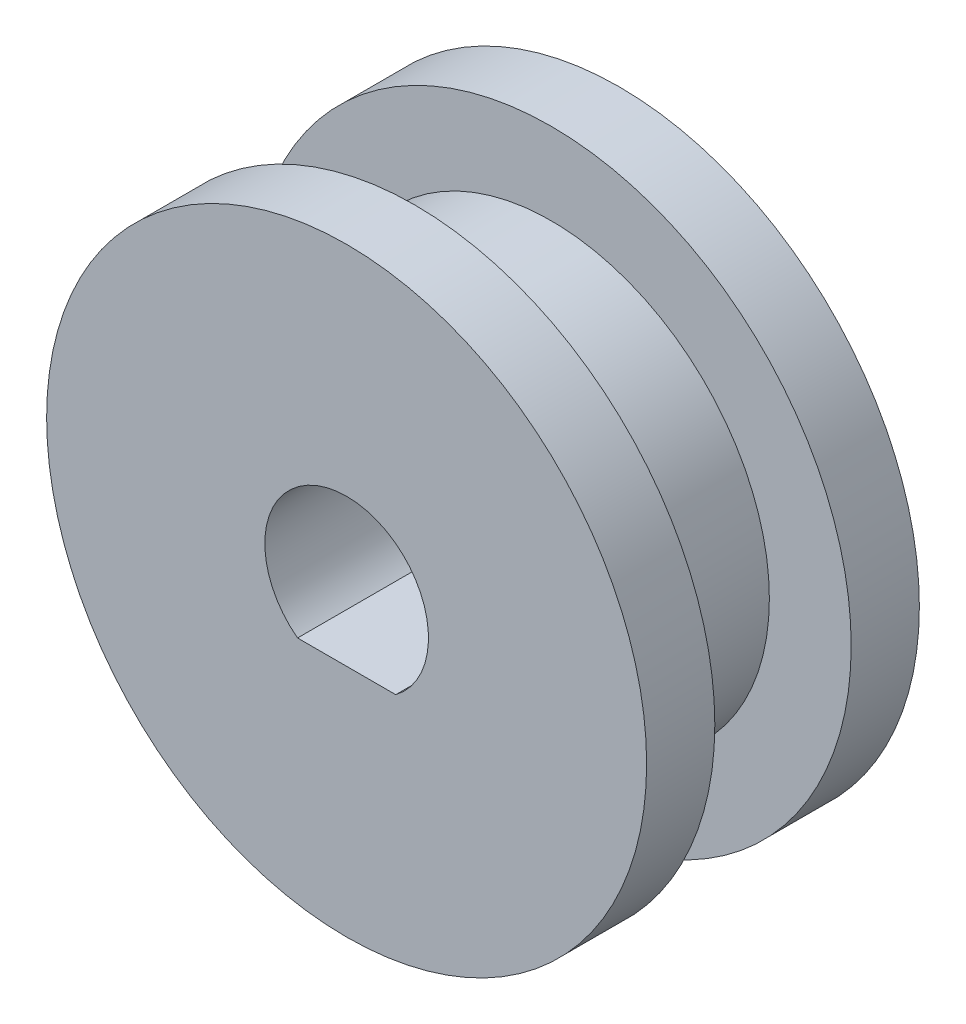
SolidWorks part; units mm, degrees
material "Nylon 101"
ref_plane "Front" through (0, 0, 0) normal (0, 0, 1) x (1, 0, 0)
ref_plane "Top" through (0, 0, 0) normal (0, 1, 0) x (1, 0, 0)
ref_plane "Right" through (0, 0, 0) normal (1, 0, 0) x (0, 0, -1)
sketch "Sketch1" plane through (0, 0, 0) normal (0, 0, 1) x (1, 0, 0)
  line L0 (-1.8, -2.4) -> (1.8, -2.4)
  arc A0 (1.8, -2.4) -> (-1.8, -2.4) centre (0, 0) ccw
  circle A1 centre (0, 0) radius 11
  dimension "D1" = 6
  dimension "D3" = 22
  dimension "D2" = 3.6
extrude "Boss-Extrude1" add sketch "Sketch1" along normal blind 10 contours A1 A0 L0
sketch "Sketch2" plane through (0, 0, 0) normal (0, 1, 0) x (1, 0, 0)
  line L0 (-11, -2.5) -> (-11, -7.5)
  line L1 (-11, 0) -> (-11, -10) construction
  line L2 (-11, -7.5) -> (-8, -7.5)
  line L3 (-8, -7.5) -> (-8, -2.5)
  line L4 (-8, -2.5) -> (-11, -2.5)
  line L5 (0, 0) -> (0, -10) construction
  line L6 (11, 0) -> (-11, 0) construction
  line L7 (-11, -10) -> (11, -10) construction
  line L8 (0, -5) -> (-0.788, -5) construction
  dimension "D1" = 5
  dimension "D2" = 3
revolve "Cut-Revolve1" cut sketch "Sketch2" angle 360 about L5
